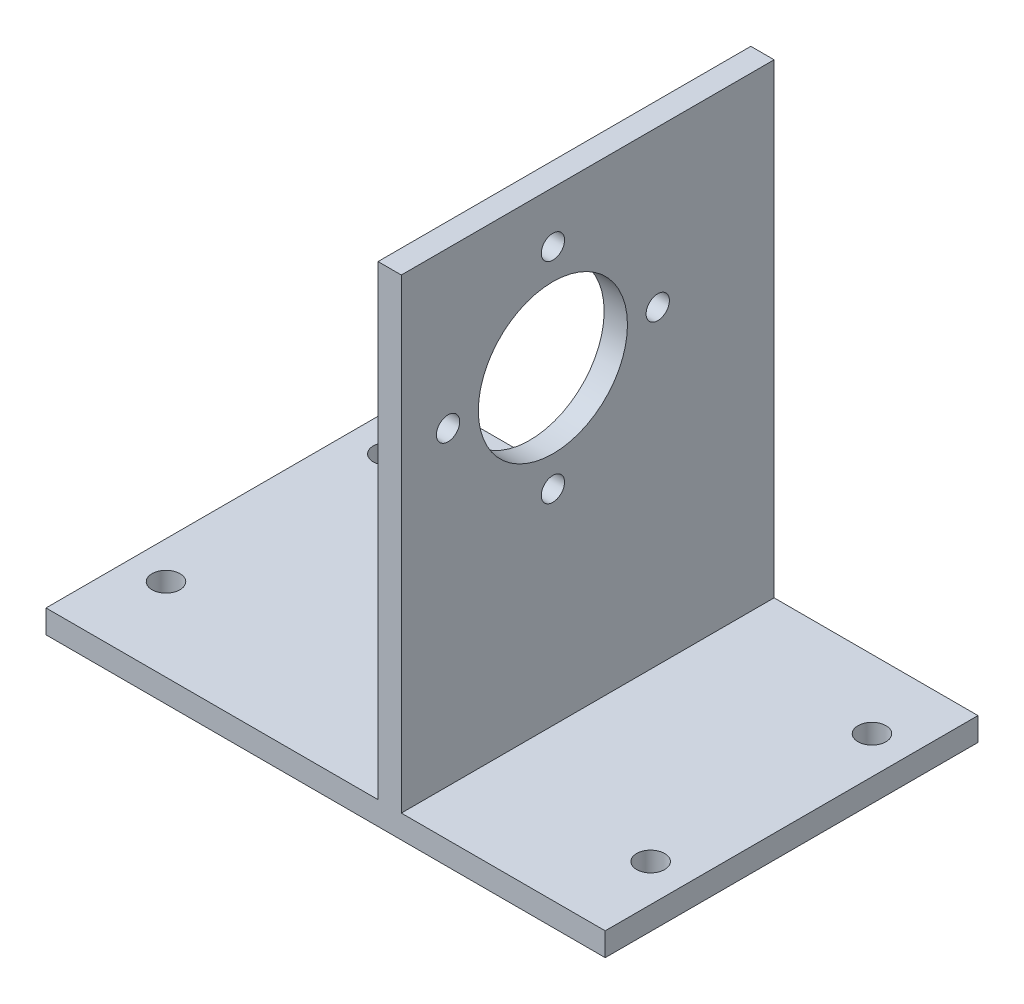
SolidWorks part; units mm, degrees
ref_plane "Front Plane" through (0, 0, 0) normal (0, 0, 1) x (1, 0, 0)
ref_plane "Top Plane" through (0, 0, 0) normal (0, 1, 0) x (1, 0, 0)
ref_plane "Right Plane" through (0, 0, 0) normal (1, 0, 0) x (0, 0, -1)
sketch "Sketch1" plane through (0, 0, 0) normal (0, 1, 0) x (1, 0, 0)
  line L0 (-60, 40) -> (60, -40) construction
  line L1 (-60, 40) -> (60, 40)
  line L2 (-60, 40) -> (-60, -40)
  line L3 (-60, -40) -> (60, -40)
  line L4 (60, 40) -> (60, -40)
  line L5 (-52, 25.25) -> (-52, -22.25) construction
  line L6 (-52, -22.25) -> (52, -22.25) construction
  line L7 (52, -22.25) -> (52, 25.25) construction
  line L8 (52, 25.25) -> (-52, 25.25) construction
  circle A0 centre (-52, 25.25) radius 3
  circle A1 centre (-52, -22.25) radius 3
  circle A2 centre (52, -22.25) radius 3
  circle A3 centre (52, 25.25) radius 3
  point P12 (-57.5666, -44.588)
  point P13 (62.4334, 35.3293)
  point P14 (0, 0)
  point P15 (0, 0)
  point P16 (51.3778, -30.0226)
  point P19 (-49.6969, 24.0793)
  point P22 (0, 0)
  point P29 (54.4334, 24.3457)
  point P30 (54.4334, -23.9626)
  point P31 (54.4334, -23.4207)
  point P32 (-49.5666, -25.3534)
  dimension "D7" = 6
  dimension "D1" = 104
  dimension "D2" = 47.5
  dimension "D3" = 8
  dimension "D4" = 14.75
  dimension "D5" = 80
  dimension "D6" = 120
extrude "Boss-Extrude1" add sketch "Sketch1" along normal blind 5
sketch "Sketch2" plane through (0, 5, 0) normal (0, 1, 0) x (1, 0, 0)
  line L0 (60, 40) -> (-60, 40) construction
  line L1 (11.25, 40) -> (16.25, 40)
  line L2 (11.25, 40) -> (11.25, -40)
  line L3 (11.25, -40) -> (16.25, -40)
  line L4 (16.25, 40) -> (16.25, -40)
  line L5 (-60, -40) -> (60, -40) construction
  dimension "D1" = 5
  dimension "D2" = 16.25
extrude "Boss-Extrude2" add sketch "Sketch2" along normal blind 100
sketch "Sketch3" plane through (16.25, 0, 0) normal (1, 0, 0) x (0, 0, -1)
  line L0 (-29.9738, 71.5) -> (-7.4738, 71.5) construction
  line L1 (-7.4738, 71.5) -> (-7.4738, 49) construction
  line L2 (-7.4738, 94) -> (-7.4738, 71.5) construction
  line L3 (-7.4738, 71.5) -> (15.0262, 71.5) construction
  circle A0 centre (-7.4738, 71.5) radius 16
  circle A2 centre (-29.9738, 71.5) radius 2.5
  circle A3 centre (15.0262, 71.5) radius 2.5
  circle A4 centre (-7.4738, 49) radius 2.5
  circle A5 centre (-7.4738, 94) radius 2.5
  circle A6 centre (-7.4738, 71.5) radius 26 construction
  dimension "D1" = 5
  dimension "D2" = 32
  dimension "D3" = 52
  dimension "D4" = 71.5
  dimension "D5" = 7.4738
  dimension "D6" = 22.5
extrude "Cut-Extrude1" cut sketch "Sketch3" against normal through all and the other way through all
